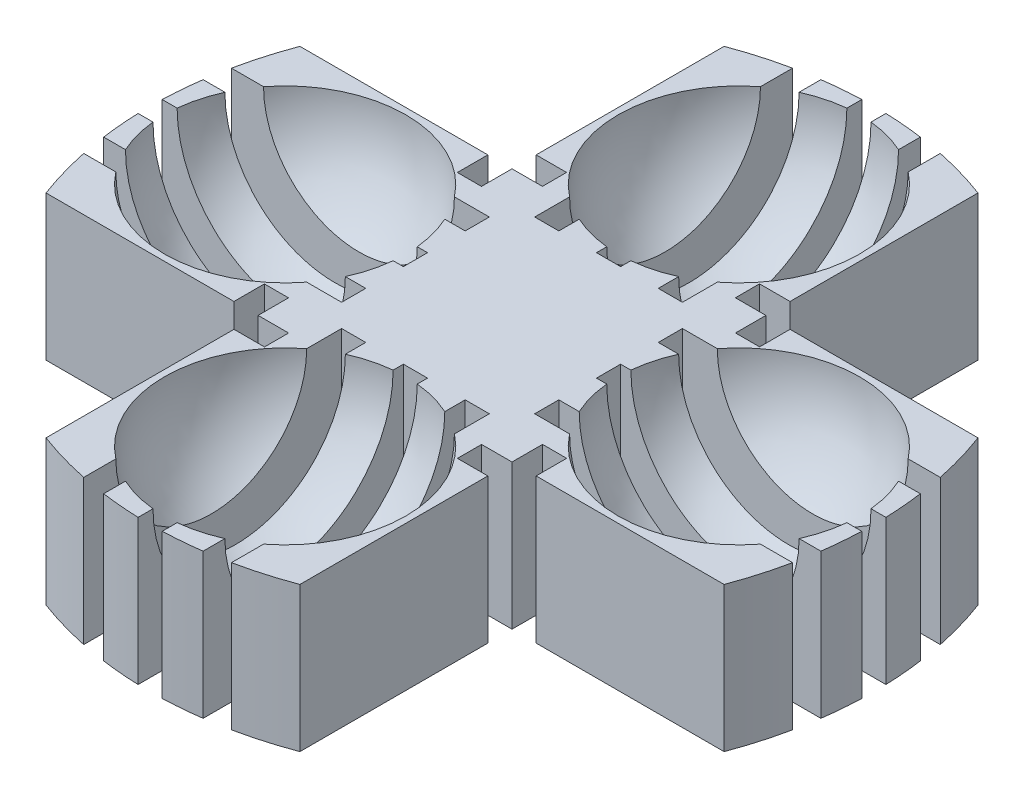
SolidWorks part; units mm, degrees
ref_plane "Front Plane" through (0, 0, 0) normal (0, 0, 1) x (1, 0, 0)
ref_plane "Top Plane" through (0, 0, 0) normal (0, 1, 0) x (1, 0, 0)
ref_plane "Right Plane" through (0, 0, 0) normal (1, 0, 0) x (0, 0, -1)
sketch "Sketch1" plane through (0, 0, 0) normal (0, 1, 0) x (1, 0, 0)
  line L0 (-33.4445, 89.1854) -> (-33.4445, 33.6962)
  line L1 (33.4445, 89.1854) -> (33.4445, 33.6962)
  line L2 (-89.0906, 33.6962) -> (-33.4445, 33.6962)
  line L3 (-89.0906, -33.6962) -> (-33.4445, -33.6962)
  line L4 (33.4445, 33.6962) -> (89.0906, 33.6962)
  line L5 (33.4445, -33.6962) -> (89.0906, -33.6962)
  line L6 (-33.4445, -33.6962) -> (-33.4445, -89.1854)
  line L7 (33.4445, -33.6962) -> (33.4445, -89.1854)
  arc A0 (-33.4445, -89.1854) -> (33.4445, -89.1854) centre (0, 0) ccw
  arc A1 (-89.0906, 33.6962) -> (-89.0906, -33.6962) centre (0, 0) ccw
  arc A2 (33.4445, 89.1854) -> (-33.4445, 89.1854) centre (0, 0) ccw
  arc A3 (89.0906, -33.6962) -> (89.0906, 33.6962) centre (0, 0) ccw
extrude "Boss-Extrude1" add sketch "Sketch1" against normal blind 38.1
ref_plane "Plane1" through (0, 0, 59.69) normal (0, 0, 1) x (1, 0, 0)
sketch "Sketch3" plane through (0, 0, 59.69) normal (0, 0, 1) x (1, 0, 0)
  line L0 (0, 0) -> (0, -31.75)
  line L1 (0, 0) -> (31.75, 0)
  arc A0 (0, -31.75) -> (31.75, 0) centre (0, 0) ccw
revolve "Cut-Revolve3" cut sketch "Sketch3" angle 360 about L0
sketch "Sketch7" plane through (0, 0, 0) normal (0, 1, 0) x (1, 0, 0)
  line L0 (-19.431, -25.4) -> (-13.081, -25.4)
  line L21 (-3.175, -25.4) -> (3.175, -25.4)
  line L22 (-3.175, -25.4) -> (-3.175, -127)
  line L23 (-3.175, -127) -> (3.175, -127)
  line L24 (3.175, -25.4) -> (3.175, -127)
  line L25 (-19.431, -25.4) -> (-19.431, -127)
  line L26 (-19.431, -127) -> (-13.081, -127)
  line L27 (-13.081, -25.4) -> (-13.081, -127)
  line L28 (13.081, -25.4) -> (19.431, -25.4)
  line L29 (13.081, -25.4) -> (13.081, -126.2754)
  line L30 (13.081, -126.2754) -> (19.431, -126.2754)
  line L31 (19.431, -25.4) -> (19.431, -126.2754)
  line L32 (33.401, -25.3712) -> (39.751, -25.3712)
  line L33 (33.401, -25.3712) -> (33.401, -126.9712)
  line L34 (33.401, -126.9712) -> (39.751, -126.9712)
  line L35 (39.751, -25.3712) -> (39.751, -126.9712)
  line L36 (-39.751, -25.4) -> (-33.401, -25.4)
  line L37 (-39.751, -25.4) -> (-39.751, -127)
  line L38 (-39.751, -127) -> (-33.401, -127)
  line L39 (-33.401, -25.4) -> (-33.401, -127)
  point P4 (0, -25.4)
  dimension "D1" = 0
  dimension "D2" = 6.35
  dimension "D3" = 101.6
  dimension "D4" = 25.4
  dimension "D5" = 20.32
  dimension "D6" = 20.32
  dimension "D7" = 16.256
  dimension "D8" = 16.256
  dimension "D9" = 0
  dimension "D10" = 0
  dimension "D11" = 0
extrude "Cut-Extrude1" cut sketch "Sketch7" against normal through all
sketch "Sketch9" plane through (0, 0, 0) normal (0, 0, 1) x (1, 0, 0)
  line L0 (0, 4.4133) -> (0, -93.6332) construction
pattern_circular "CirPattern1" count 4 over 360 about axis through (0, 0, 0) along (0, 1, 0) of "Cut-Extrude1", "Cut-Revolve3"
